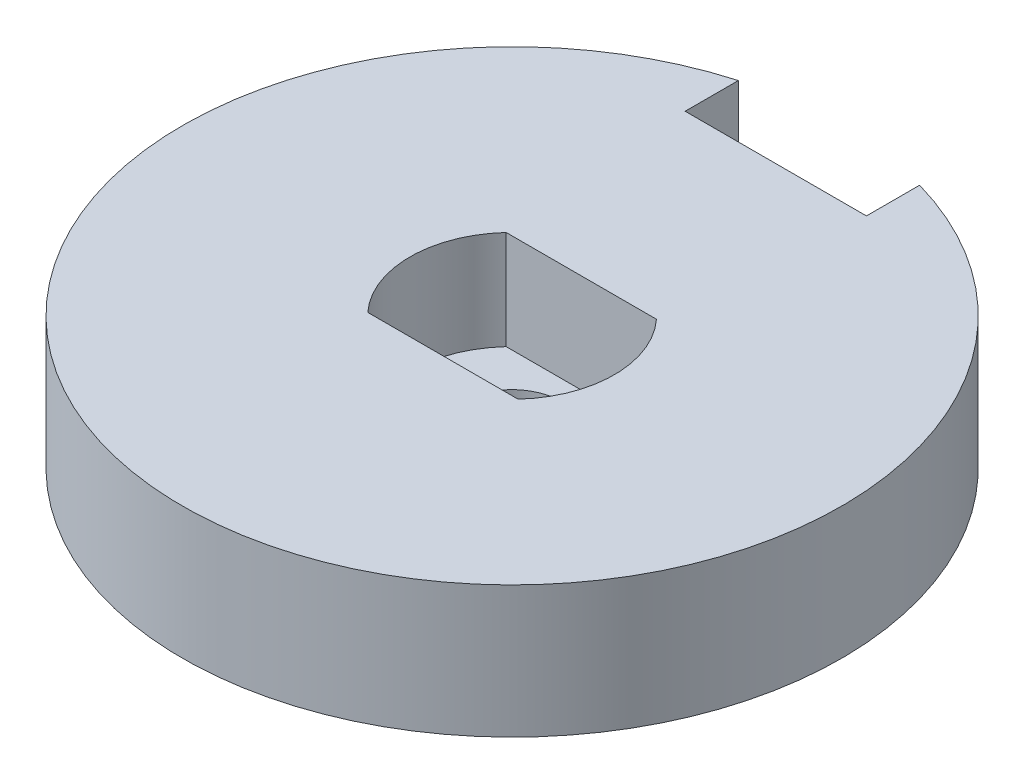
SolidWorks part; units mm, degrees
ref_plane "前视基准面" through (0, 0, 0) normal (0, 0, 1) x (1, 0, 0)
ref_plane "上视基准面" through (0, 0, 0) normal (0, 1, 0) x (1, 0, 0)
ref_plane "右视基准面" through (0, 0, 0) normal (1, 0, 0) x (0, 0, -1)
sketch "草图1" plane through (0, 0, 0) normal (0, 1, 0) x (1, 0, 0)
  line L1 (2.3706, -2.5259) -> (3.3728, 0.7901)
  line L2 (3.3728, 0.7901) -> (1.0021, 3.316)
  line L3 (1.0021, 3.316) -> (-2.3706, 2.5259)
  line L4 (-2.3706, 2.5259) -> (-3.3728, -0.7901)
  line L5 (-3.3728, -0.7901) -> (-1.0021, -3.316)
  line L6 (-1.0021, -3.316) -> (2.3706, -2.5259)
  circle A0 centre (0, 0) radius 3 construction
  dimension "D1" = 6
extrude "凸台-拉伸1" add sketch "草图1" along normal blind 3.5
sketch "草图3" plane through (0, 3.5, 0) normal (0, 1, 0) x (1, 0, 0)
  line L0 (0, 0) -> (0, 8) construction
  line L1 (-2.75, 8) -> (2.75, 8)
  line L2 (-2.75, 8) -> (-2.75, 9.6144)
  line L3 (2.75, 8) -> (2.75, 9.6144)
  arc A0 (-2.75, 9.6144) -> (2.75, 9.6144) centre (0, 0) ccw
  point P7 (0, 8)
  dimension "D1" = 20
  dimension "D2" = 8
  dimension "D3" = 5.5
extrude "凸台-拉伸2" add sketch "草图3" along normal blind 4
sketch "草图4" plane through (0, 0, 0) normal (0, -1, 0) x (1, 0, 0)
  circle A0 centre (0, 0) radius 1.5
  dimension "D1" = 3
extrude "切除-拉伸1" cut sketch "草图4" against normal blind 4
sketch "草图5" plane through (0, 7.5, 0) normal (0, 1, 0) x (1, 0, 0)
  line L0 (0, 0) -> (0, 2.1) construction
  line L1 (-2.2804, 2.1) -> (2.2804, 2.1)
  line L2 (0, 0) -> (1.7805, 0) construction
  line L3 (-2.2804, -2.1) -> (2.2804, -2.1)
  arc A0 (-2.2804, 2.1) -> (-2.2804, -2.1) centre (0, 0) ccw
  arc A1 (2.2804, -2.1) -> (2.2804, 2.1) centre (0, 0) ccw
  dimension "D1" = 6.2
  dimension "D2" = 2.1
extrude "切除-拉伸2" cut sketch "草图5" against normal blind 3
sketch "草图6" plane through (0, 0, 0) normal (0, -1, 0) x (1, 0, 0)
  circle A0 centre (0, 0) radius 1.5
extrude "切除-拉伸3" cut sketch "草图6" against normal through all
sketch "草图7" plane through (0, 7.5, 0) normal (0, 1, 0) x (1, 0, 0)
  line L0 (0, 8) -> (0, 3.5) construction
  line L1 (2.75, 8) -> (-2.75, 8) construction
  line L2 (-2, 3.5) -> (2, 3.5)
  line L3 (2, 3.5) -> (2, 8)
  line L4 (2, 8) -> (-2, 8)
  line L5 (-2, 3.5) -> (-2, 8)
  dimension "D1" = 4.5
  dimension "D2" = 2
extrude "切除-拉伸4" cut sketch "草图7" against normal blind 0.9
ref_plane "基准面1" through (0, 5.5, 0) normal (0, 1, 0) x (1, 0, 0)
mirror "镜向1" about plane through (0, 5.5, 0) normal (0, 1, 0) of "切除-拉伸4"
sketch "草图8" plane through (0, 6.6, 0) normal (0, 1, 0) x (1, 0, 0)
  line L1 (-2, 8) -> (2, 8)
  line L2 (-2, 8) -> (-2, 3.5)
  line L3 (-2, 3.5) -> (2, 3.5)
  line L4 (2, 8) -> (2, 3.5)
  line L5 (-2, 8) -> (2, 3.5) construction
  line L6 (-2, 3.5) -> (2, 8) construction
  point P0 (0, 5.75)
extrude "凸台-拉伸3" add sketch "草图8" along normal up to surface (0.9 mm away) up to face at (0, 7.5, -4.8268)
